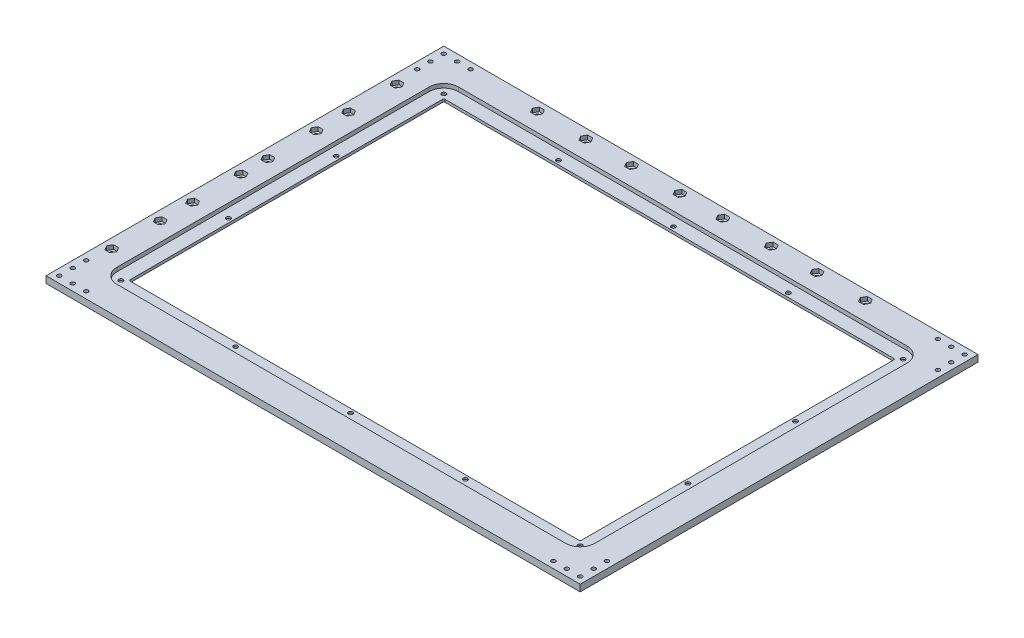
SolidWorks part; units mm, degrees
ref_plane "Front Plane" through (0, 0, 0) normal (0, 0, 1) x (1, 0, 0)
ref_plane "Top Plane" through (0, 0, 0) normal (0, 1, 0) x (1, 0, 0)
ref_plane "Right Plane" through (0, 0, 0) normal (1, 0, 0) x (0, 0, -1)
sketch "Sketch1" plane through (0, 0, 0) normal (0, 1, 0) x (1, 0, 0)
  line L1 (0, 0) -> (399.5, 0)
  line L2 (0, 0) -> (0, 297.5)
  line L3 (0, 297.5) -> (399.5, 297.5)
  line L4 (399.5, 0) -> (399.5, 297.5)
  dimension "D1" = 297.5
  dimension "D2" = 399.5
extrude "Boss-Extrude1" add sketch "Sketch1" along normal blind 5
sketch "Sketch2" plane through (0, 0, 0) normal (0, -1, 0) x (1, 0, 0)
  line L0 (399.5, 0) -> (0, 0)
  line L1 (199.75, 0) -> (199.75, -297.5)
  line L2 (399.5, -297.5) -> (0, -297.5) construction
  line L3 (0, -297.5) -> (0, 0)
  line L4 (0, -148.75) -> (399.5, -148.75)
  line L5 (399.5, 0) -> (399.5, -297.5) construction
  circle A0 centre (31, -5) radius 1.6 construction
  circle A1 centre (10, -5) radius 1.6 construction
  circle A2 centre (5, -10) radius 1.6 construction
  circle A3 centre (5, -31) radius 1.6 construction
  circle A4 centre (31, -5) radius 1.6
  circle A5 centre (10, -5) radius 1.6
  circle A6 centre (5, -10) radius 1.6
  circle A7 centre (5, -31) radius 1.6
  circle A8 centre (394.5, -31) radius 1.6
  circle A9 centre (394.5, -10) radius 1.6
  circle A10 centre (389.5, -5) radius 1.6
  circle A11 centre (368.5, -5) radius 1.6
  circle A12 centre (31, -292.5) radius 1.6
  circle A13 centre (10, -292.5) radius 1.6
  circle A14 centre (5, -287.5) radius 1.6
  circle A15 centre (5, -266.5) radius 1.6
  circle A16 centre (368.5, -292.5) radius 1.6
  circle A17 centre (389.5, -292.5) radius 1.6
  circle A18 centre (394.5, -287.5) radius 1.6
  circle A19 centre (394.5, -266.5) radius 1.6
extrude "Cut-Extrude2" cut sketch "Sketch2" against normal blind 1.2 contours A4 | A5 | A6 | A7 | A8 | A9 | A10 | A11 | A12 | A13 | A14 | A15 | A18 | A17 | A16 | A19
sketch "Sketch3" plane through (0, 0, 0) normal (0, -1, 0) x (1, 0, 0)
  circle A0 centre (25, -5) radius 1.5 construction
  circle A1 centre (15, -5) radius 1.5 construction
  circle A2 centre (5, -15) radius 1.5 construction
  circle A3 centre (5, -25) radius 1.5 construction
  circle A4 centre (5, -272.5) radius 1.5 construction
  circle A5 centre (5, -282.5) radius 1.5 construction
  circle A6 centre (15, -292.5) radius 1.5 construction
  circle A7 centre (25, -292.5) radius 1.5 construction
  circle A8 centre (374.5, -5) radius 1.5 construction
  circle A9 centre (384.5, -5) radius 1.5 construction
  circle A10 centre (394.5, -15) radius 1.5 construction
  circle A11 centre (394.5, -25) radius 1.5 construction
  circle A12 centre (394.5, -272.5) radius 1.5 construction
  circle A13 centre (394.5, -282.5) radius 1.5 construction
  circle A14 centre (384.5, -292.5) radius 1.5 construction
  circle A15 centre (374.5, -292.5) radius 1.5 construction
  circle A16 centre (25, -5) radius 1.5
  circle A17 centre (15, -5) radius 1.5
  circle A18 centre (5, -15) radius 1.5
  circle A19 centre (5, -25) radius 1.5
  circle A20 centre (5, -272.5) radius 1.5
  circle A21 centre (5, -282.5) radius 1.5
  circle A22 centre (15, -292.5) radius 1.5
  circle A23 centre (25, -292.5) radius 1.5
  circle A24 centre (374.5, -5) radius 1.5
  circle A25 centre (384.5, -5) radius 1.5
  circle A26 centre (394.5, -15) radius 1.5
  circle A27 centre (394.5, -25) radius 1.5
  circle A28 centre (394.5, -272.5) radius 1.5
  circle A29 centre (394.5, -282.5) radius 1.5
  circle A30 centre (384.5, -292.5) radius 1.5
  circle A31 centre (374.5, -292.5) radius 1.5
extrude "Cut-Extrude3" cut sketch "Sketch3" against normal blind 59.2
sketch "Sketch4" plane through (0, 5, 0) normal (0, 1, 0) x (1, 0, 0)
  circle A0 centre (5, 5) radius 1.5 construction
  circle A1 centre (394.5, 292.5) radius 1.5 construction
  circle A2 centre (394.5, 5) radius 1.5 construction
  circle A3 centre (5, 292.5) radius 1.5 construction
  circle A4 centre (5, 5) radius 1.5
  circle A5 centre (394.5, 292.5) radius 1.5
  circle A6 centre (394.5, 5) radius 1.5
  circle A7 centre (5, 292.5) radius 1.5
extrude "Cut-Extrude4" cut sketch "Sketch4" against normal blind 10.2
sketch "Sketch5" plane through (0, 5, 0) normal (0, 1, 0) x (1, 0, 0)
  line L0 (0, 297.5) -> (0, 0) construction
  line L1 (32, 276.5) -> (367.5, 276.5)
  line L2 (21, 265.5) -> (21, 32)
  line L3 (32, 21) -> (367.5, 21)
  line L4 (378.5, 265.5) -> (378.5, 32)
  line L5 (399.5, 297.5) -> (0, 297.5) construction
  line L6 (399.5, 0) -> (399.5, 297.5) construction
  line L7 (0, 0) -> (399.5, 0) construction
  arc A0 (378.5, 32) -> (367.5, 21) centre (367.5, 32) cw
  arc A1 (378.5, 265.5) -> (367.5, 276.5) centre (367.5, 265.5) ccw
  arc A2 (32, 276.5) -> (21, 265.5) centre (32, 265.5) ccw
  arc A3 (21, 32) -> (32, 21) centre (32, 32) ccw
  dimension "D5" = 11
  dimension "D1" = 21
  dimension "D2" = 21
  dimension "D3" = 21
  dimension "D4" = 21
extrude "Cut-Extrude5" cut sketch "Sketch5" against normal blind 3
sketch "Sketch6" plane through (0, 2, 0) normal (0, 1, 0) x (1, 0, 0)
  line L0 (368.5, 32) -> (368.5, 265.5)
  line L1 (367.5, 266.5) -> (32, 266.5)
  line L2 (31, 265.5) -> (31, 32)
  line L3 (32, 31) -> (367.5, 31)
  line L4 (378.5, 32) -> (378.5, 265.5)
  line L5 (367.5, 276.5) -> (32, 276.5)
  line L6 (21, 265.5) -> (21, 32)
  line L7 (32, 21) -> (367.5, 21)
  line L8 (378.5, 32) -> (378.5, 265.5)
  line L9 (367.5, 276.5) -> (32, 276.5)
  line L10 (21, 265.5) -> (21, 32)
  line L11 (32, 21) -> (367.5, 21)
  arc A0 (367.5, 31) -> (368.5, 32) centre (367.5, 32) ccw
  arc A1 (368.5, 265.5) -> (367.5, 266.5) centre (367.5, 265.5) ccw
  arc A2 (32, 266.5) -> (31, 265.5) centre (32, 265.5) ccw
  arc A3 (31, 32) -> (32, 31) centre (32, 32) ccw
  arc A4 (367.5, 21) -> (378.5, 32) centre (367.5, 32) ccw
  arc A5 (378.5, 265.5) -> (367.5, 276.5) centre (367.5, 265.5) ccw
  arc A6 (32, 276.5) -> (21, 265.5) centre (32, 265.5) ccw
  arc A7 (21, 32) -> (32, 21) centre (32, 32) ccw
  arc A8 (367.5, 21) -> (378.5, 32) centre (367.5, 32) ccw
  arc A9 (378.5, 265.5) -> (367.5, 276.5) centre (367.5, 265.5) ccw
  arc A10 (32, 276.5) -> (21, 265.5) centre (32, 265.5) ccw
  arc A11 (21, 32) -> (32, 21) centre (32, 32) ccw
  dimension "D1" = 0
  dimension "D2" = 10
extrude "Cut-Extrude6" cut sketch "Sketch6" against normal blind 13 contours L1 A2 L2 A3 L3 A0 L0 A1
sketch "Sketch9" plane through (0, 2, 0) normal (0, 1, 0) x (1, 0, 0)
  circle A0 centre (199.75, 28) radius 1.6 construction
  circle A1 centre (285.625, 28) radius 1.6 construction
  circle A2 centre (371.5, 28) radius 1.6 construction
  circle A3 centre (371.5, 108.5) radius 1.6 construction
  circle A4 centre (371.5, 189) radius 1.6 construction
  circle A5 centre (113.875, 28) radius 1.6 construction
  circle A6 centre (28, 28) radius 1.6 construction
  circle A7 centre (28, 108.5) radius 1.6 construction
  circle A8 centre (28, 189) radius 1.6 construction
  circle A9 centre (28, 269.5) radius 1.6 construction
  circle A10 centre (113.875, 269.5) radius 1.6 construction
  circle A11 centre (199.75, 269.5) radius 1.6 construction
  circle A12 centre (285.625, 269.5) radius 1.6 construction
  circle A13 centre (371.5, 269.5) radius 1.6 construction
  circle A14 centre (199.75, 28) radius 1.6
  circle A15 centre (285.625, 28) radius 1.6
  circle A16 centre (371.5, 28) radius 1.6
  circle A17 centre (371.5, 108.5) radius 1.6
  circle A18 centre (371.5, 189) radius 1.6
  circle A19 centre (113.875, 28) radius 1.6
  circle A20 centre (28, 28) radius 1.6
  circle A21 centre (28, 108.5) radius 1.6
  circle A22 centre (28, 189) radius 1.6
  circle A23 centre (28, 269.5) radius 1.6
  circle A24 centre (113.875, 269.5) radius 1.6
  circle A25 centre (199.75, 269.5) radius 1.6
  circle A26 centre (285.625, 269.5) radius 1.6
  circle A27 centre (371.5, 269.5) radius 1.6
extrude "Cut-Extrude7" cut sketch "Sketch9" against normal blind 1.2
sketch "Sketch11" plane through (0, 0, 0) normal (0, -1, 0) x (1, 0, 0)
  circle A0 centre (286.2, -290.4) radius 1.6 construction
  circle A1 centre (322.4, -290.4) radius 1.6 construction
  circle A2 centre (252, -290.4) radius 1.6 construction
  circle A3 centre (215.8, -290.4) radius 1.6 construction
  circle A4 centre (183.7, -290.4) radius 1.6 construction
  circle A5 centre (147.5, -290.4) radius 1.6 construction
  circle A6 centre (113.3, -290.4) radius 1.6 construction
  circle A7 centre (77.1, -290.4) radius 1.6 construction
  circle A8 centre (7.1, -255.4) radius 1.6 construction
  circle A9 centre (7.1, -219.2) radius 1.6 construction
  circle A10 centre (7.1, -195) radius 1.6 construction
  circle A11 centre (7.1, -158.8) radius 1.6 construction
  circle A12 centre (7.1, -138.7) radius 1.6 construction
  circle A13 centre (7.1, -102.5) radius 1.6 construction
  circle A14 centre (7.1, -78.3) radius 1.6 construction
  circle A15 centre (7.1, -42.1) radius 1.6 construction
  circle A16 centre (286.2, -290.4) radius 1.6
  circle A17 centre (322.4, -290.4) radius 1.6
  circle A18 centre (252, -290.4) radius 1.6
  circle A19 centre (215.8, -290.4) radius 1.6
  circle A20 centre (183.7, -290.4) radius 1.6
  circle A21 centre (147.5, -290.4) radius 1.6
  circle A22 centre (113.3, -290.4) radius 1.6
  circle A23 centre (77.1, -290.4) radius 1.6
  circle A24 centre (7.1, -255.4) radius 1.6
  circle A25 centre (7.1, -219.2) radius 1.6
  circle A26 centre (7.1, -195) radius 1.6
  circle A27 centre (7.1, -158.8) radius 1.6
  circle A28 centre (7.1, -138.7) radius 1.6
  circle A29 centre (7.1, -102.5) radius 1.6
  circle A30 centre (7.1, -78.3) radius 1.6
  circle A31 centre (7.1, -42.1) radius 1.6
extrude "Cut-Extrude8" cut sketch "Sketch11" against normal blind 10
sketch "Sketch12" plane through (0, 5, 0) normal (0, 1, 0) x (1, 0, 0)
  line L1 (326.19, 290.4) -> (324.295, 293.6822)
  line L2 (324.295, 293.6822) -> (320.505, 293.6822)
  line L3 (320.505, 293.6822) -> (318.61, 290.4)
  line L4 (318.61, 290.4) -> (320.505, 287.1178)
  line L5 (320.505, 287.1178) -> (324.295, 287.1178)
  line L6 (324.295, 287.1178) -> (326.19, 290.4)
  line L7 (289.99, 290.4) -> (288.095, 293.6822)
  line L8 (288.095, 293.6822) -> (284.305, 293.6822)
  line L9 (284.305, 293.6822) -> (282.41, 290.4)
  line L10 (282.41, 290.4) -> (284.305, 287.1178)
  line L11 (284.305, 287.1178) -> (288.095, 287.1178)
  line L12 (288.095, 287.1178) -> (289.99, 290.4)
  line L13 (248.21, 290.4) -> (250.105, 287.1178)
  line L14 (250.105, 287.1178) -> (253.895, 287.1178)
  line L15 (253.895, 287.1178) -> (255.79, 290.4)
  line L16 (255.79, 290.4) -> (253.895, 293.6822)
  line L17 (253.895, 293.6822) -> (250.105, 293.6822)
  line L18 (250.105, 293.6822) -> (248.21, 290.4)
  line L19 (212.01, 290.4) -> (213.905, 287.1178)
  line L20 (213.905, 287.1178) -> (217.695, 287.1178)
  line L21 (217.695, 287.1178) -> (219.59, 290.4)
  line L22 (219.59, 290.4) -> (217.695, 293.6822)
  line L23 (217.695, 293.6822) -> (213.905, 293.6822)
  line L24 (213.905, 293.6822) -> (212.01, 290.4)
  line L25 (179.91, 290.4) -> (181.805, 287.1178)
  line L26 (181.805, 287.1178) -> (185.595, 287.1178)
  line L27 (185.595, 287.1178) -> (187.49, 290.4)
  line L28 (187.49, 290.4) -> (185.595, 293.6822)
  line L29 (185.595, 293.6822) -> (181.805, 293.6822)
  line L30 (181.805, 293.6822) -> (179.91, 290.4)
  line L31 (143.71, 290.4) -> (145.605, 287.1178)
  line L32 (145.605, 287.1178) -> (149.395, 287.1178)
  line L33 (149.395, 287.1178) -> (151.29, 290.4)
  line L34 (151.29, 290.4) -> (149.395, 293.6822)
  line L35 (149.395, 293.6822) -> (145.605, 293.6822)
  line L36 (145.605, 293.6822) -> (143.71, 290.4)
  line L37 (109.51, 290.4) -> (111.405, 287.1178)
  line L38 (111.405, 287.1178) -> (115.195, 287.1178)
  line L39 (115.195, 287.1178) -> (117.09, 290.4)
  line L40 (117.09, 290.4) -> (115.195, 293.6822)
  line L41 (115.195, 293.6822) -> (111.405, 293.6822)
  line L42 (111.405, 293.6822) -> (109.51, 290.4)
  line L43 (73.31, 290.4) -> (75.205, 287.1178)
  line L44 (75.205, 287.1178) -> (78.995, 287.1178)
  line L45 (78.995, 287.1178) -> (80.89, 290.4)
  line L46 (80.89, 290.4) -> (78.995, 293.6822)
  line L47 (78.995, 293.6822) -> (75.205, 293.6822)
  line L48 (75.205, 293.6822) -> (73.31, 290.4)
  circle A0 centre (322.4, 290.4) radius 3.2822 construction
  circle A1 centre (286.2, 290.4) radius 3.2822 construction
  circle A2 centre (252, 290.4) radius 3.2822 construction
  circle A3 centre (215.8, 290.4) radius 3.2822 construction
  circle A4 centre (183.7, 290.4) radius 3.2822 construction
  circle A5 centre (147.5, 290.4) radius 3.2822 construction
  circle A6 centre (113.3, 290.4) radius 3.2822 construction
  circle A7 centre (77.1, 290.4) radius 3.2822 construction
  dimension "D1" = 7.58
  dimension "D2" = 7.58
  dimension "D3" = 7.58
  dimension "D4" = 7.58
  dimension "D5" = 7.58
  dimension "D6" = 7.58
  dimension "D7" = 7.58
  dimension "D8" = 7.58
extrude "Cut-Extrude9" cut sketch "Sketch12" against normal blind 3
sketch "Sketch13" plane through (0, 5, 0) normal (0, 1, 0) x (1, 0, 0)
  line L1 (10.89, 255.4) -> (8.995, 258.6822)
  line L2 (8.995, 258.6822) -> (5.205, 258.6822)
  line L3 (5.205, 258.6822) -> (3.31, 255.4)
  line L4 (3.31, 255.4) -> (5.205, 252.1178)
  line L5 (5.205, 252.1178) -> (8.995, 252.1178)
  line L6 (8.995, 252.1178) -> (10.89, 255.4)
  line L7 (10.89, 219.2) -> (8.995, 222.4822)
  line L8 (8.995, 222.4822) -> (5.205, 222.4822)
  line L9 (5.205, 222.4822) -> (3.31, 219.2)
  line L10 (3.31, 219.2) -> (5.205, 215.9178)
  line L11 (5.205, 215.9178) -> (8.995, 215.9178)
  line L12 (8.995, 215.9178) -> (10.89, 219.2)
  line L13 (10.89, 195) -> (8.995, 198.2822)
  line L14 (8.995, 198.2822) -> (5.205, 198.2822)
  line L15 (5.205, 198.2822) -> (3.31, 195)
  line L16 (3.31, 195) -> (5.205, 191.7178)
  line L17 (5.205, 191.7178) -> (8.995, 191.7178)
  line L18 (8.995, 191.7178) -> (10.89, 195)
  line L19 (10.89, 158.8) -> (8.995, 162.0822)
  line L20 (8.995, 162.0822) -> (5.205, 162.0822)
  line L21 (5.205, 162.0822) -> (3.31, 158.8)
  line L22 (3.31, 158.8) -> (5.205, 155.5178)
  line L23 (5.205, 155.5178) -> (8.995, 155.5178)
  line L24 (8.995, 155.5178) -> (10.89, 158.8)
  line L25 (10.89, 138.7) -> (8.995, 141.9822)
  line L26 (8.995, 141.9822) -> (5.205, 141.9822)
  line L27 (5.205, 141.9822) -> (3.31, 138.7)
  line L28 (3.31, 138.7) -> (5.205, 135.4178)
  line L29 (5.205, 135.4178) -> (8.995, 135.4178)
  line L30 (8.995, 135.4178) -> (10.89, 138.7)
  line L31 (10.89, 102.5) -> (8.995, 105.7822)
  line L32 (8.995, 105.7822) -> (5.205, 105.7822)
  line L33 (5.205, 105.7822) -> (3.31, 102.5)
  line L34 (3.31, 102.5) -> (5.205, 99.2178)
  line L35 (5.205, 99.2178) -> (8.995, 99.2178)
  line L36 (8.995, 99.2178) -> (10.89, 102.5)
  line L37 (10.89, 78.3) -> (8.995, 81.5822)
  line L38 (8.995, 81.5822) -> (5.205, 81.5822)
  line L39 (5.205, 81.5822) -> (3.31, 78.3)
  line L40 (3.31, 78.3) -> (5.205, 75.0178)
  line L41 (5.205, 75.0178) -> (8.995, 75.0178)
  line L42 (8.995, 75.0178) -> (10.89, 78.3)
  line L43 (10.89, 42.1) -> (8.995, 45.3822)
  line L44 (8.995, 45.3822) -> (5.205, 45.3822)
  line L45 (5.205, 45.3822) -> (3.31, 42.1)
  line L46 (3.31, 42.1) -> (5.205, 38.8178)
  line L47 (5.205, 38.8178) -> (8.995, 38.8178)
  line L48 (8.995, 38.8178) -> (10.89, 42.1)
  circle A0 centre (7.1, 255.4) radius 3.2822 construction
  circle A1 centre (7.1, 219.2) radius 3.2822 construction
  circle A2 centre (7.1, 195) radius 3.2822 construction
  circle A3 centre (7.1, 158.8) radius 3.2822 construction
  circle A4 centre (7.1, 138.7) radius 3.2822 construction
  circle A5 centre (7.1, 102.5) radius 3.2822 construction
  circle A6 centre (7.1, 78.3) radius 3.2822 construction
  circle A7 centre (7.1, 42.1) radius 3.2822 construction
  dimension "D1" = 7.58
  dimension "D2" = 7.58
  dimension "D3" = 7.58
  dimension "D4" = 7.58
  dimension "D5" = 7.58
  dimension "D6" = 7.58
  dimension "D7" = 7.58
  dimension "D8" = 7.58
extrude "Cut-Extrude10" cut sketch "Sketch13" against normal blind 3
